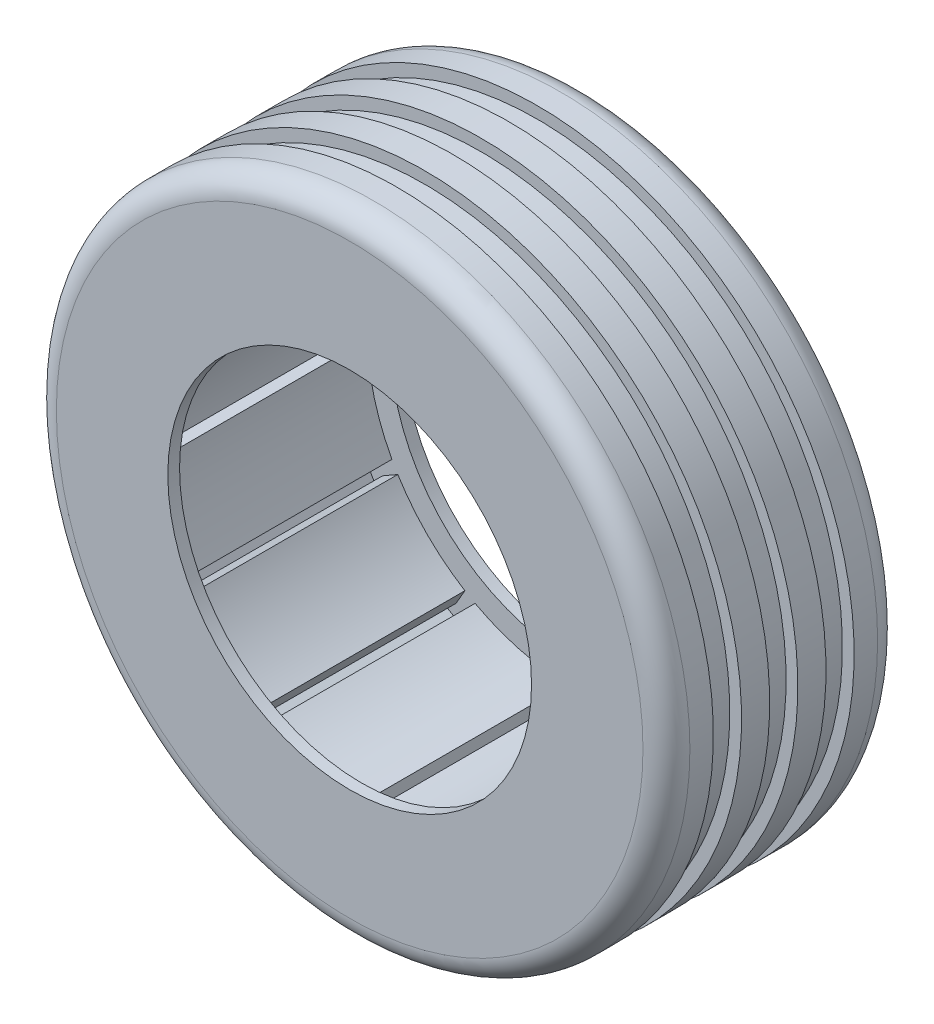
SolidWorks part; units mm, degrees
material "硅橡胶"
ref_plane "前视基准面" through (0, 0, 0) normal (0, 0, 1) x (1, 0, 0)
ref_plane "上视基准面" through (0, 0, 0) normal (0, 1, 0) x (1, 0, 0)
ref_plane "右视基准面" through (0, 0, 0) normal (1, 0, 0) x (0, 0, -1)
sketch "草图1" plane through (0, 0, 0) normal (0, 0, 1) x (1, 0, 0)
  circle A0 centre (0, 0) radius 27
  dimension "D1" = 54
extrude "凸台-拉伸1" add sketch "草图1" along normal mid plane 20
fillet "圆角1" radius 2 2 edges at (27, 0, -10) (27, 0, 10)
sketch "草图3" plane through (0, 0, 0) normal (0, 0, 1) x (1, 0, 0)
  circle A0 centre (0, 0) radius 17.5
  dimension "D1" = 35
extrude "切除-拉伸1" cut sketch "草图3" against normal mid plane 18
sketch "草图5" plane through (0, 0, 10) normal (0, 0, 1) x (1, 0, 0)
  circle A0 centre (0, 0) radius 15.5
  dimension "D1" = 31
extrude "切除-拉伸2" cut sketch "草图5" against normal through all
sketch "草图6" plane through (0, 0, 0) normal (0, 0, 1) x (1, 0, 0)
  line L0 (0, 0) -> (0, 33.0676) construction
  line L1 (0.5, 17.4929) -> (0.5, 19)
  line L2 (0.5, 19) -> (2, 19)
  line L3 (2, 19) -> (2, 20)
  line L4 (2, 20) -> (-2, 20)
  line L5 (-0.5, 17.4929) -> (-0.5, 19)
  line L6 (-2, 19) -> (-2, 20)
  line L7 (-0.5, 19) -> (-2, 19)
  arc A0 (0.5, 17.4929) -> (-0.5, 17.4929) centre (0, 0) ccw
  point P9 (0, 17.5)
  point P13 (0, 20)
  dimension "D1" = 35
  dimension "D2" = 1
  dimension "D3" = 0.5
  dimension "D4" = 2.5
  dimension "D5" = 2
extrude "切除-拉伸3" cut sketch "草图6" against normal mid plane 18
pattern_circular "阵列(圆周)1" count 12 over 360 about axis through (0, 0, 0) along (0, 0, 1) of "切除-拉伸3"
sketch "草图7" plane through (0, 0, -10) normal (0, 0, -1) x (-1, 0, 0)
  circle A0 centre (0, 0) radius 26
  circle A1 centre (0, 0) radius 30.4279
  dimension "D1" = 52
extrude "切除-拉伸4" cut sketch "草图7" against normal blind 2.4 from offset 4 offset against normal yes
sketch "草图9" plane through (0, 0, 0) normal (0, 1, 0) x (1, 0, 0)
  line L0 (0, 15.696) -> (0, 0) construction
pattern_linear "阵列(线性)1" count 3 spacing 4.8 along (0, 0, 1) of "切除-拉伸4"
